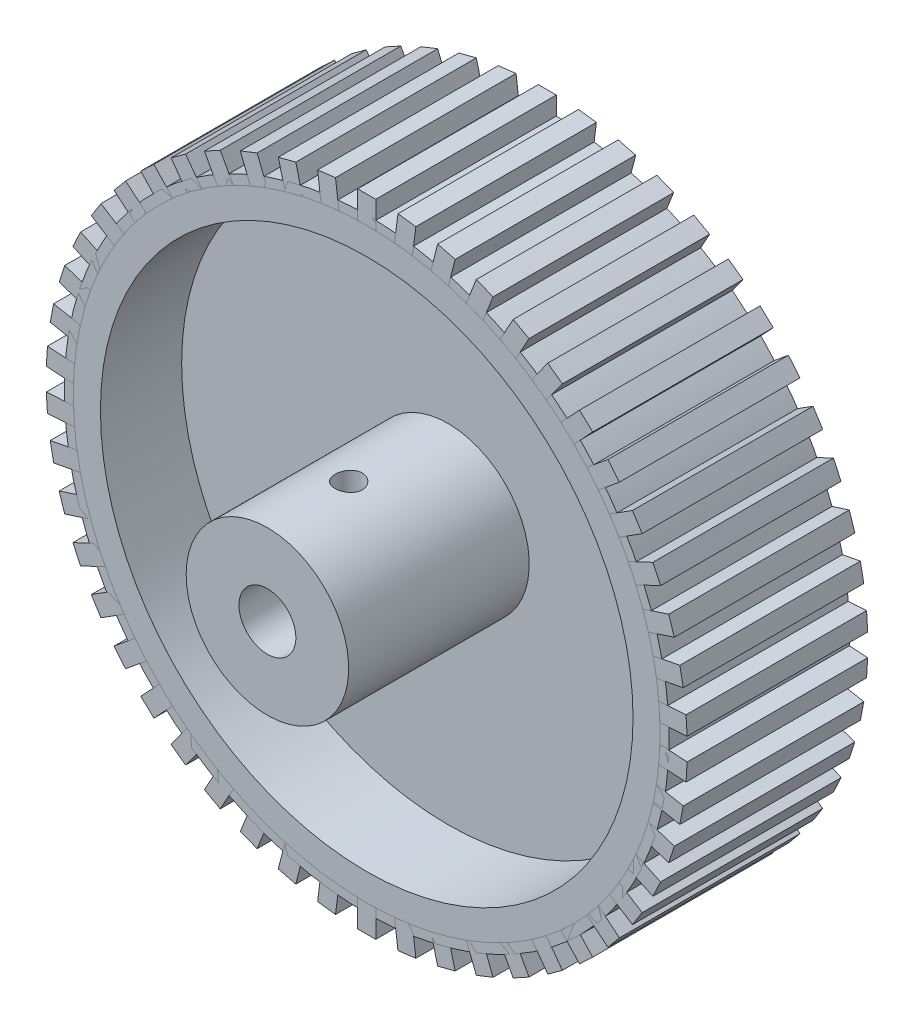
SolidWorks part; units mm, degrees
ref_plane "Front Plane" through (0, 0, 0) normal (0, 0, 1) x (1, 0, 0)
ref_plane "Top Plane" through (0, 0, 0) normal (0, 1, 0) x (1, 0, 0)
ref_plane "Right Plane" through (0, 0, 0) normal (1, 0, 0) x (0, 0, -1)
sketch "Sketch1" plane through (0, 0, 0) normal (1, 0, 0) x (0, 0, -1)
  line L0 (0, 0) -> (-15.3329, 0) construction
  line L1 (0, 3.15) -> (-22, 3.15)
  line L2 (-22, 3.15) -> (-22, 9)
  line L3 (-22, 9) -> (-2, 9)
  line L4 (-2, 9) -> (-2, 29.5)
  line L5 (-2, 29.5) -> (-11, 29.5)
  line L6 (-11, 29.5) -> (-11, 32.5)
  line L8 (0, 29.5) -> (0, 3.15)
  line L9 (-11, 32.5) -> (9, 32.5)
  line L12 (0, 29.5) -> (9, 29.5)
  line L13 (9, 32.5) -> (9, 29.5)
  line L14 (-2, 19.25) -> (0, 19.25) construction
  line L15 (-1, 19.25) -> (-1, 32.5) construction
  point P17 (4.5, 29.5)
  point P18 (0, 16.325)
  dimension "D1" = 3.15
  dimension "D2" = 9
  dimension "D4" = 20
  dimension "D3" = 20
  dimension "D5" = 32.5
  dimension "D6" = 3
  dimension "D7" = 2
revolve "Revolve1" add sketch "Sketch1" angle 360 about L0
sketch "Sketch2" plane through (0, 0, 0) normal (0, 1, 0) x (1, 0, 0)
  line L0 (0, -22) -> (0, -13) construction
  line L1 (-3.15, -22) -> (3.15, -22) construction
  circle A0 centre (0, -13) radius 1.5
  point P7 (0, 0)
  point P8 (0, 0)
  dimension "D2" = 3
  dimension "D1" = 9
extrude "Cut-Extrude1" cut sketch "Sketch2" along normal blind 10
sketch "Sketch3" plane through (0, 0, 11) normal (0, 0, 1) x (1, 0, 0)
  circle A4 centre (0, 0) radius 32.5
  circle A6 centre (0, 0) radius 33.5
  circle A7 centre (0, 0) radius 32.5 construction
  dimension "D1" = 1
extrude "Boss-Extrude1" add sketch "Sketch3" against normal up to surface (20 mm away) separate body up to face at (-32.5, 0, -9)
sketch "Sketch4" plane through (0, 0, -9) normal (0, 0, -1) x (-1, 0, 0)
  line L0 (0, 0) -> (0, 37.0219) construction
  line L1 (3.4572, 35.3454) -> (3.0793, 32.3538)
  line L2 (-1, 35.5) -> (1, 35.5)
  line L3 (-1, 35.5) -> (-1, 32.4846)
  line L4 (-1, 32.4846) -> (1, 32.4846)
  line L5 (1, 35.5) -> (1, 32.4846)
  line L6 (3.4572, 35.3454) -> (5.4414, 35.0947)
  line L7 (5.4414, 35.0947) -> (5.0635, 32.1031)
  line L8 (3.0793, 32.3538) -> (5.0635, 32.1031)
  line L9 (7.8599, 34.6334) -> (7.11, 31.7127)
  line L10 (7.8599, 34.6334) -> (9.7971, 34.136)
  line L11 (9.7971, 34.136) -> (9.0472, 31.2154)
  line L12 (7.11, 31.7127) -> (9.0472, 31.2154)
  line L13 (12.1386, 33.3752) -> (11.0286, 30.5716)
  line L14 (12.1386, 33.3752) -> (13.9982, 32.6389)
  line L15 (13.9982, 32.6389) -> (12.8882, 29.8353)
  line L16 (11.0286, 30.5716) -> (12.8882, 29.8353)
  line L17 (16.2259, 31.5906) -> (14.7733, 28.9482)
  line L18 (16.2259, 31.5906) -> (17.9786, 30.6271)
  line L19 (17.9786, 30.6271) -> (16.5259, 27.9847)
  line L20 (14.7733, 28.9482) -> (16.5259, 27.9847)
  line L21 (20.0574, 29.3079) -> (18.285, 26.8684)
  line L22 (20.0574, 29.3079) -> (21.6754, 28.1323)
  line L23 (21.6754, 28.1323) -> (19.903, 25.6928)
  line L24 (18.285, 26.8684) -> (19.903, 25.6928)
  line L25 (23.5725, 26.5629) -> (21.5083, 24.3648)
  line L26 (23.5725, 26.5629) -> (25.0304, 25.1938)
  line L27 (25.0304, 25.1938) -> (22.9662, 22.9957)
  line L28 (21.5083, 24.3648) -> (22.9662, 22.9957)
  line L29 (26.7158, 23.3991) -> (24.3924, 21.477)
  line L30 (26.7158, 23.3991) -> (27.9906, 21.858)
  line L31 (27.9906, 21.858) -> (25.6672, 19.936)
  line L32 (24.3924, 21.477) -> (25.6672, 19.936)
  line L33 (29.4378, 19.8662) -> (26.8918, 18.2505)
  line L34 (29.4378, 19.8662) -> (30.5095, 18.1775)
  line L35 (30.5095, 18.1775) -> (27.9635, 16.5618)
  line L36 (26.8918, 18.2505) -> (27.9635, 16.5618)
  line L37 (31.6956, 16.02) -> (28.9672, 14.7361)
  line L38 (31.6956, 16.02) -> (32.5471, 14.2103)
  line L39 (32.5471, 14.2103) -> (29.8187, 12.9264)
  line L40 (28.9672, 14.7361) -> (29.8187, 12.9264)
  line L41 (33.4535, 11.9212) -> (30.5857, 10.9894)
  line L42 (33.4535, 11.9212) -> (34.0715, 10.019)
  line L43 (34.0715, 10.019) -> (31.2037, 9.0872)
  line L44 (30.5857, 10.9894) -> (31.2037, 9.0872)
  line L45 (34.6838, 7.6343) -> (31.7218, 7.0693)
  line L46 (34.6838, 7.6343) -> (35.0586, 5.6697)
  line L47 (35.0586, 5.6697) -> (32.0966, 5.1047)
  line L48 (31.7218, 7.0693) -> (32.0966, 5.1047)
  line L49 (35.3672, 3.2271) -> (32.3577, 3.0378)
  line L50 (35.3672, 3.2271) -> (35.4927, 1.231)
  line L51 (35.4927, 1.231) -> (32.4833, 1.0417)
  line L52 (32.3577, 3.0378) -> (32.4833, 1.0417)
  line L53 (35.4927, -1.231) -> (32.4833, -1.0417)
  line L54 (35.4927, -1.231) -> (35.3672, -3.2271)
  line L55 (35.3672, -3.2271) -> (32.3577, -3.0378)
  line L56 (32.4833, -1.0417) -> (32.3577, -3.0378)
  line L57 (35.0586, -5.6697) -> (32.0966, -5.1047)
  line L58 (35.0586, -5.6697) -> (34.6838, -7.6343)
  line L59 (34.6838, -7.6343) -> (31.7218, -7.0693)
  line L60 (32.0966, -5.1047) -> (31.7218, -7.0693)
  line L61 (34.0715, -10.019) -> (31.2037, -9.0872)
  line L62 (34.0715, -10.019) -> (33.4535, -11.9212)
  line L63 (33.4535, -11.9212) -> (30.5857, -10.9894)
  line L64 (31.2037, -9.0872) -> (30.5857, -10.9894)
  line L65 (32.5471, -14.2103) -> (29.8187, -12.9264)
  line L66 (32.5471, -14.2103) -> (31.6956, -16.02)
  line L67 (31.6956, -16.02) -> (28.9672, -14.7361)
  line L68 (29.8187, -12.9264) -> (28.9672, -14.7361)
  line L69 (30.5095, -18.1775) -> (27.9635, -16.5618)
  line L70 (30.5095, -18.1775) -> (29.4378, -19.8662)
  line L71 (29.4378, -19.8662) -> (26.8918, -18.2505)
  line L72 (27.9635, -16.5618) -> (26.8918, -18.2505)
  line L73 (27.9906, -21.858) -> (25.6672, -19.936)
  line L74 (27.9906, -21.858) -> (26.7158, -23.3991)
  line L75 (26.7158, -23.3991) -> (24.3924, -21.477)
  line L76 (25.6672, -19.936) -> (24.3924, -21.477)
  line L77 (25.0304, -25.1938) -> (22.9662, -22.9957)
  line L78 (25.0304, -25.1938) -> (23.5725, -26.5629)
  line L79 (23.5725, -26.5629) -> (21.5083, -24.3648)
  line L80 (22.9662, -22.9957) -> (21.5083, -24.3648)
  line L81 (21.6754, -28.1323) -> (19.903, -25.6928)
  line L82 (21.6754, -28.1323) -> (20.0574, -29.3079)
  line L83 (20.0574, -29.3079) -> (18.285, -26.8684)
  line L84 (19.903, -25.6928) -> (18.285, -26.8684)
  line L85 (17.9786, -30.6271) -> (16.5259, -27.9847)
  line L86 (17.9786, -30.6271) -> (16.2259, -31.5906)
  line L87 (16.2259, -31.5906) -> (14.7733, -28.9482)
  line L88 (16.5259, -27.9847) -> (14.7733, -28.9482)
  line L89 (13.9982, -32.6389) -> (12.8882, -29.8353)
  line L90 (13.9982, -32.6389) -> (12.1386, -33.3752)
  line L91 (12.1386, -33.3752) -> (11.0286, -30.5716)
  line L92 (12.8882, -29.8353) -> (11.0286, -30.5716)
  line L93 (9.7971, -34.136) -> (9.0472, -31.2154)
  line L94 (9.7971, -34.136) -> (7.8599, -34.6334)
  line L95 (7.8599, -34.6334) -> (7.11, -31.7127)
  line L96 (9.0472, -31.2154) -> (7.11, -31.7127)
  line L97 (5.4414, -35.0947) -> (5.0635, -32.1031)
  line L98 (5.4414, -35.0947) -> (3.4572, -35.3454)
  line L99 (3.4572, -35.3454) -> (3.0793, -32.3538)
  line L100 (5.0635, -32.1031) -> (3.0793, -32.3538)
  line L101 (1, -35.5) -> (1, -32.4846)
  line L102 (1, -35.5) -> (-1, -35.5)
  line L103 (-1, -35.5) -> (-1, -32.4846)
  line L104 (1, -32.4846) -> (-1, -32.4846)
  line L105 (-3.4572, -35.3454) -> (-3.0793, -32.3538)
  line L106 (-3.4572, -35.3454) -> (-5.4414, -35.0947)
  line L107 (-5.4414, -35.0947) -> (-5.0635, -32.1031)
  line L108 (-3.0793, -32.3538) -> (-5.0635, -32.1031)
  line L109 (-7.8599, -34.6334) -> (-7.11, -31.7127)
  line L110 (-7.8599, -34.6334) -> (-9.7971, -34.136)
  line L111 (-9.7971, -34.136) -> (-9.0472, -31.2154)
  line L112 (-7.11, -31.7127) -> (-9.0472, -31.2154)
  line L113 (-12.1386, -33.3752) -> (-11.0286, -30.5716)
  line L114 (-12.1386, -33.3752) -> (-13.9982, -32.6389)
  line L115 (-13.9982, -32.6389) -> (-12.8882, -29.8353)
  line L116 (-11.0286, -30.5716) -> (-12.8882, -29.8353)
  line L117 (-16.2259, -31.5906) -> (-14.7733, -28.9482)
  line L118 (-16.2259, -31.5906) -> (-17.9786, -30.6271)
  line L119 (-17.9786, -30.6271) -> (-16.5259, -27.9847)
  line L120 (-14.7733, -28.9482) -> (-16.5259, -27.9847)
  line L121 (-20.0574, -29.3079) -> (-18.285, -26.8684)
  line L122 (-20.0574, -29.3079) -> (-21.6754, -28.1323)
  line L123 (-21.6754, -28.1323) -> (-19.903, -25.6928)
  line L124 (-18.285, -26.8684) -> (-19.903, -25.6928)
  line L125 (-23.5725, -26.5629) -> (-21.5083, -24.3648)
  line L126 (-23.5725, -26.5629) -> (-25.0304, -25.1938)
  line L127 (-25.0304, -25.1938) -> (-22.9662, -22.9957)
  line L128 (-21.5083, -24.3648) -> (-22.9662, -22.9957)
  line L129 (-26.7158, -23.3991) -> (-24.3924, -21.477)
  line L130 (-26.7158, -23.3991) -> (-27.9906, -21.858)
  line L131 (-27.9906, -21.858) -> (-25.6672, -19.936)
  line L132 (-24.3924, -21.477) -> (-25.6672, -19.936)
  line L133 (-29.4378, -19.8662) -> (-26.8918, -18.2505)
  line L134 (-29.4378, -19.8662) -> (-30.5095, -18.1775)
  line L135 (-30.5095, -18.1775) -> (-27.9635, -16.5618)
  line L136 (-26.8918, -18.2505) -> (-27.9635, -16.5618)
  line L137 (-31.6956, -16.02) -> (-28.9672, -14.7361)
  line L138 (-31.6956, -16.02) -> (-32.5471, -14.2103)
  line L139 (-32.5471, -14.2103) -> (-29.8187, -12.9264)
  line L140 (-28.9672, -14.7361) -> (-29.8187, -12.9264)
  line L141 (-33.4535, -11.9212) -> (-30.5857, -10.9894)
  line L142 (-33.4535, -11.9212) -> (-34.0715, -10.019)
  line L143 (-34.0715, -10.019) -> (-31.2037, -9.0872)
  line L144 (-30.5857, -10.9894) -> (-31.2037, -9.0872)
  line L145 (-34.6838, -7.6343) -> (-31.7218, -7.0693)
  line L146 (-34.6838, -7.6343) -> (-35.0586, -5.6697)
  line L147 (-35.0586, -5.6697) -> (-32.0966, -5.1047)
  line L148 (-31.7218, -7.0693) -> (-32.0966, -5.1047)
  line L149 (-35.3672, -3.2271) -> (-32.3577, -3.0378)
  line L150 (-35.3672, -3.2271) -> (-35.4927, -1.231)
  line L151 (-35.4927, -1.231) -> (-32.4833, -1.0417)
  line L152 (-32.3577, -3.0378) -> (-32.4833, -1.0417)
  line L153 (-35.4927, 1.231) -> (-32.4833, 1.0417)
  line L154 (-35.4927, 1.231) -> (-35.3672, 3.2271)
  line L155 (-35.3672, 3.2271) -> (-32.3577, 3.0378)
  line L156 (-32.4833, 1.0417) -> (-32.3577, 3.0378)
  line L157 (-35.0586, 5.6697) -> (-32.0966, 5.1047)
  line L158 (-35.0586, 5.6697) -> (-34.6838, 7.6343)
  line L159 (-34.6838, 7.6343) -> (-31.7218, 7.0693)
  line L160 (-32.0966, 5.1047) -> (-31.7218, 7.0693)
  line L161 (-34.0715, 10.019) -> (-31.2037, 9.0872)
  line L162 (-34.0715, 10.019) -> (-33.4535, 11.9212)
  line L163 (-33.4535, 11.9212) -> (-30.5857, 10.9894)
  line L164 (-31.2037, 9.0872) -> (-30.5857, 10.9894)
  line L165 (-32.5471, 14.2103) -> (-29.8187, 12.9264)
  line L166 (-32.5471, 14.2103) -> (-31.6956, 16.02)
  line L167 (-31.6956, 16.02) -> (-28.9672, 14.7361)
  line L168 (-29.8187, 12.9264) -> (-28.9672, 14.7361)
  line L169 (-30.5095, 18.1775) -> (-27.9635, 16.5618)
  line L170 (-30.5095, 18.1775) -> (-29.4378, 19.8662)
  line L171 (-29.4378, 19.8662) -> (-26.8918, 18.2505)
  line L172 (-27.9635, 16.5618) -> (-26.8918, 18.2505)
  line L173 (-27.9906, 21.858) -> (-25.6672, 19.936)
  line L174 (-27.9906, 21.858) -> (-26.7158, 23.3991)
  line L175 (-26.7158, 23.3991) -> (-24.3924, 21.477)
  line L176 (-25.6672, 19.936) -> (-24.3924, 21.477)
  line L177 (-25.0304, 25.1938) -> (-22.9662, 22.9957)
  line L178 (-25.0304, 25.1938) -> (-23.5725, 26.5629)
  line L179 (-23.5725, 26.5629) -> (-21.5083, 24.3648)
  line L180 (-22.9662, 22.9957) -> (-21.5083, 24.3648)
  line L181 (-21.6754, 28.1323) -> (-19.903, 25.6928)
  line L182 (-21.6754, 28.1323) -> (-20.0574, 29.3079)
  line L183 (-20.0574, 29.3079) -> (-18.285, 26.8684)
  line L184 (-19.903, 25.6928) -> (-18.285, 26.8684)
  line L185 (-17.9786, 30.6271) -> (-16.5259, 27.9847)
  line L186 (-17.9786, 30.6271) -> (-16.2259, 31.5906)
  line L187 (-16.2259, 31.5906) -> (-14.7733, 28.9482)
  line L188 (-16.5259, 27.9847) -> (-14.7733, 28.9482)
  line L189 (-13.9982, 32.6389) -> (-12.8882, 29.8353)
  line L190 (-13.9982, 32.6389) -> (-12.1386, 33.3752)
  line L191 (-12.1386, 33.3752) -> (-11.0286, 30.5716)
  line L192 (-12.8882, 29.8353) -> (-11.0286, 30.5716)
  line L193 (-9.7971, 34.136) -> (-9.0472, 31.2154)
  line L194 (-9.7971, 34.136) -> (-7.8599, 34.6334)
  line L195 (-7.8599, 34.6334) -> (-7.11, 31.7127)
  line L196 (-9.0472, 31.2154) -> (-7.11, 31.7127)
  line L197 (-5.4414, 35.0947) -> (-5.0635, 32.1031)
  line L198 (-5.4414, 35.0947) -> (-3.4572, 35.3454)
  line L199 (-3.4572, 35.3454) -> (-3.0793, 32.3538)
  line L200 (-5.0635, 32.1031) -> (-3.0793, 32.3538)
  circle A0 centre (0, 0) radius 32.5 construction
  circle A2 centre (0, 0) radius 33.5 construction
  point P210 (0, 0)
  dimension "D1" = 2
  dimension "D2" = 2
  dimension "D3" = 50
extrude "Boss-Extrude2" add sketch "Sketch4" against normal up to surface (20 mm away) separate body up to face at (-29.5, 0, 11)
equation "\"D5@Sketch1\"=65/2"
